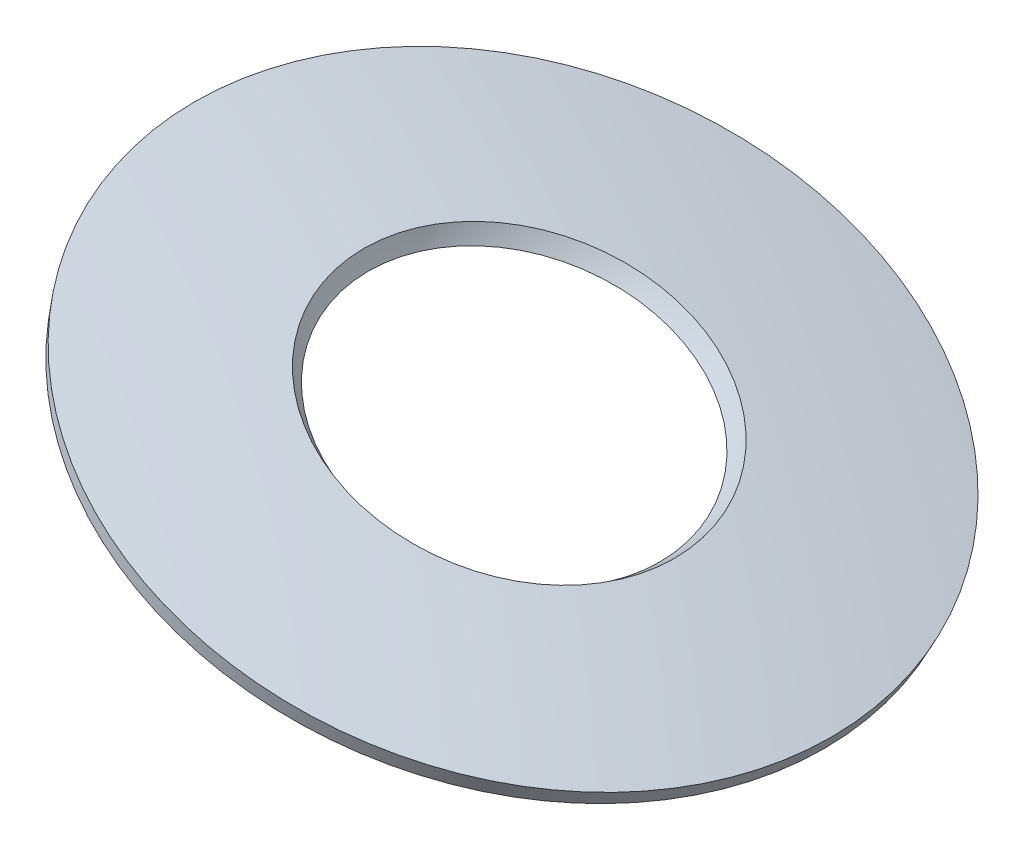
SolidWorks part; units mm, degrees
ref_plane "Front Plane" through (0, 0, 0) normal (0, 0, 1) x (1, 0, 0)
ref_plane "Top Plane" through (0, 0, 0) normal (0, 1, 0) x (1, 0, 0)
ref_plane "Right Plane" through (0, 0, 0) normal (1, 0, 0) x (0, 0, -1)
sketch "sketch1" plane through (0, 0, 0) normal (0, 0, 1) x (1, 0, 0)
  line L1 (0, 0) -> (85.505, 234.9232)
  line L2 (116.6226, 219.3352) -> (117.3679, 220.7369)
  arc A0 (117.3679, 220.7369) -> (101.2584, 228.5755) centre (0, 0) ccw
  arc A1 (116.6226, 219.3352) -> (99.7525, 227.5043) centre (0, 0) ccw
  arc A2 (99.7525, 227.5043) -> (101.2584, 228.5755) centre (88.9252, 244.3201) ccw
  dimension "D1" = 500
  dimension "D2" = 496.825
  dimension "D4" = 40
  dimension "D5" = 260
  dimension "D6" = 8
revolve "Revolve2" add sketch "sketch1" angle 360 about L1
